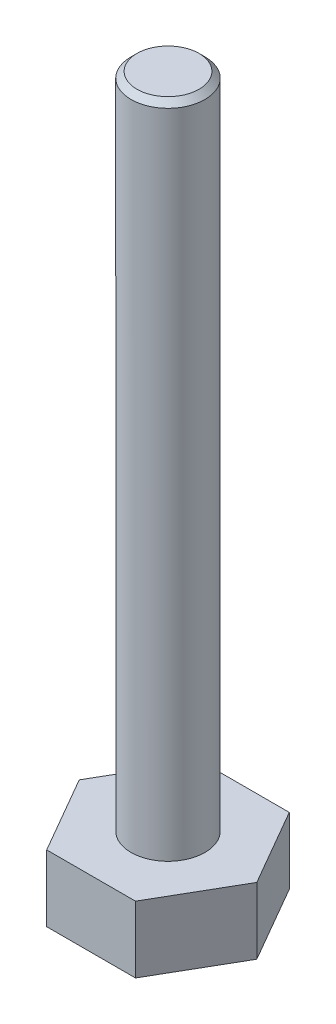
SolidWorks part; units mm, degrees
ref_plane "Front Plane" through (0, 0, 0) normal (0, 0, 1) x (1, 0, 0)
ref_plane "Top Plane" through (0, 0, 0) normal (0, 1, 0) x (1, 0, 0)
ref_plane "Right Plane" through (0, 0, 0) normal (1, 0, 0) x (0, 0, -1)
sketch "Sketch1" plane through (0, 0, 0) normal (0, 1, 0) x (1, 0, 0)
  line L1 (30.0222, -52) -> (60.0444, 0)
  line L2 (60.0444, 0) -> (30.0222, 52)
  line L3 (30.0222, 52) -> (-30.0222, 52)
  line L4 (-30.0222, 52) -> (-60.0444, 0)
  line L5 (-60.0444, 0) -> (-30.0222, -52)
  line L6 (-30.0222, -52) -> (30.0222, -52)
  circle A0 centre (0, 0) radius 52 construction
  circle A1 centre (0, 0) radius 25
  dimension "D2" = 50
  dimension "D1" = 104
extrude "Boss-Extrude1" add sketch "Sketch1" along normal blind 45
sketch "Sketch5" plane through (0, 0, 0) normal (0, -1, 0) x (1, 0, 0)
  circle A0 centre (0, 0) radius 25 construction
  circle A1 centre (0, 0) radius 25
extrude "Boss-Extrude2" add sketch "Sketch5" against normal blind 490
chamfer "Chamfer1" distance 4 angle 45 1 edges at (0, 490, -25)
